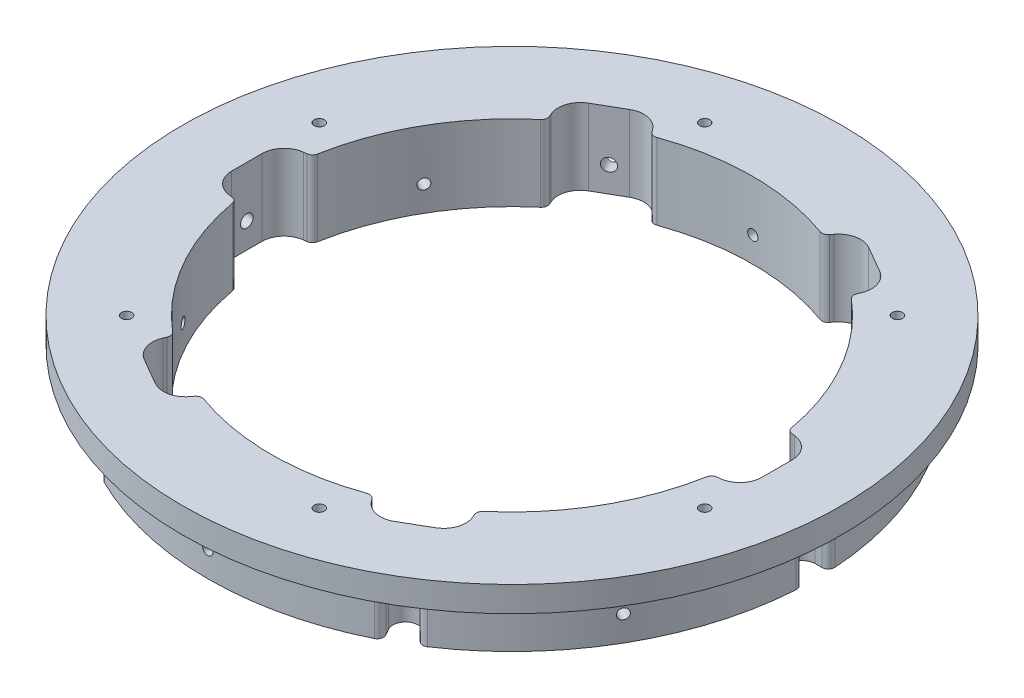
SolidWorks part; units mm, degrees
material "6061-T6 (SS)"
ref_plane "Front Plane" through (0, 0, 0) normal (0, 0, 1) x (1, 0, 0)
ref_plane "Top Plane" through (0, 0, 0) normal (0, 1, 0) x (1, 0, 0)
ref_plane "Right Plane" through (0, 0, 0) normal (1, 0, 0) x (0, 0, -1)
sketch "Sketch1" plane through (0, 0, 0) normal (0, 1, 0) x (1, 0, 0)
  circle A0 centre (0, 0) radius 76.2
  circle A1 centre (0, 0) radius 60.325
  dimension "D1" = 152.4
  dimension "D2" = 120.65
extrude "Boss-Extrude1" add sketch "Sketch1" against normal blind 19.05
sketch "Sketch3" plane through (0, -19.05, 0) normal (0, -1, 0) x (-1, 0, 0)
  line L0 (-76.1338, 3.175) -> (-72.771, 3.175)
  line L1 (-76.1338, -3.175) -> (-72.771, -3.175)
  circle A0 centre (0, 0) radius 76.2 construction
  arc A1 (-72.771, 3.175) -> (-72.771, -3.175) centre (-72.771, 0) cw
  arc A2 (-76.1338, -3.175) -> (-76.1338, 3.175) centre (0, 0) cw
  point P9 (-69.596, 0)
  point P13 (-76.2, 0)
  dimension "D1" = 6.35
  dimension "D2" = 6.604
extrude "Cut-Extrude1" cut sketch "Sketch3" against normal blind 12.7
sketch "Sketch4" plane through (0, -19.05, 0) normal (0, -1, 0) x (-1, 0, 0)
  line L0 (-66.421, 8.7312) -> (-66.421, -8.7312)
  line L1 (-66.421, -8.7312) -> (-59.5683, -9.525)
  line L2 (-59.5683, -9.525) -> (-59.5683, 9.525)
  line L3 (-59.5683, 9.525) -> (-66.421, 8.7312)
  line L4 (-66.421, 0) -> (0, 0) construction
  circle A0 centre (0, 0) radius 60.325 construction
  dimension "D1" = 3.175
  dimension "D2" = 19.05
  dimension "D3" = 17.4625
extrude "Cut-Extrude2" cut sketch "Sketch4" against normal through all
hole_wizard "1/8 (0.125) Diameter Hole1" positions "Sketch5" profile "Sketch6" hole size "1/8" standard "ANSI Inch"
sketch "Sketch5" plane through (66.421, 0, 0) normal (-1, 0, 0) x (0, 0, 1)
  line L0 (-8.7312, -19.05) -> (8.7312, -19.05) construction
  point P0 (0, -12.7)
  dimension "D1" = 6.35
sketch "Sketch6" plane through (66.421, -12.7, 0) normal (0, 1, 0) x (0, 0, 1)
  line L0 (0, 0) -> (0, 9.779)
  line L1 (0, 9.779) -> (1.5875, 9.779)
  line L2 (1.5875, 9.779) -> (1.5875, 0)
  line L5 (1.5875, 0) -> (0, 0)
  line L11 (0, -6.35) -> (0, 107.95) construction
  dimension "Thru Hole Dia." = 3.175
  dimension "Thru Hole Depth" = 9.779
fillet "Fillet1" radius 1.5875 4 edges at (76.1338, -12.7, 3.175) (76.1338, -12.7, -3.175) (59.5683, -9.525, 9.525) (59.5683, -9.525, -9.525)
fillet "Fillet2" radius 5.5562 2 edges at (66.421, -9.525, 8.7312) (66.421, -9.525, -8.7312)
sketch "Sketch9" plane through (0, 0, 0) normal (0, 0, 1) x (1, 0, 0)
  line L0 (-76.2, -19.05) -> (76.0446, -19.05) construction
  circle A0 centre (0, -12.7) radius 1.2891
  point P4 (0, 0)
  dimension "D1" = 2.5781
  dimension "D2" = 6.35
extrude "Cut-Extrude3" cut sketch "Sketch9" against normal through all
sketch "Sketch11" plane through (0, -19.05, 0) normal (0, -1, 0) x (1, 0, 0)
  line L0 (0, 0) -> (76.2, 0) construction
  line L1 (0, 0) -> (65.9365, 17.6676) construction
  line L2 (58.2695, 15.6133) -> (73.6035, 19.722) construction
  circle A0 centre (65.9365, 17.6676) radius 1.289
  arc A1 (76.0446, -4.8638) -> (76.0446, 4.8638) centre (0, 0) ccw construction
  arc A2 (59.3714, 10.6838) -> (59.3714, -10.6838) centre (0, 0) ccw construction
  arc A3 (76.0446, 4.8638) -> (76.0446, -4.8638) centre (0, 0) ccw construction
  point P16 (0, 0)
  point P17 (0, 0)
  point P18 (65.9365, 17.6676)
  dimension "D1" = 2.5781
  dimension "D2" = 15
extrude "Cut-Extrude5" cut sketch "Sketch11" against normal through all
pattern_circular "CirPattern1" count 6 over 360 about axis through (0, 0, 0) along (0, 1, 0) of "Cut-Extrude1", "Cut-Extrude2", "Fillet2", "Fillet1", "1/8 (0.125) Diameter Hole1", "Cut-Extrude3", "Cut-Extrude5"
sketch "Sketch8" plane through (0, 0, 0) normal (0, 1, 0) x (1, 0, 0)
  circle A0 centre (0, 0) radius 82.55
  circle A1 centre (0, 0) radius 76.2
  circle A2 centre (0, 0) radius 76.2 construction
  dimension "D1" = 6.35
extrude "Boss-Extrude3" add sketch "Sketch8" against normal up to surface (6.35 mm away) up to face at (-74.0439, -6.35, 0)
